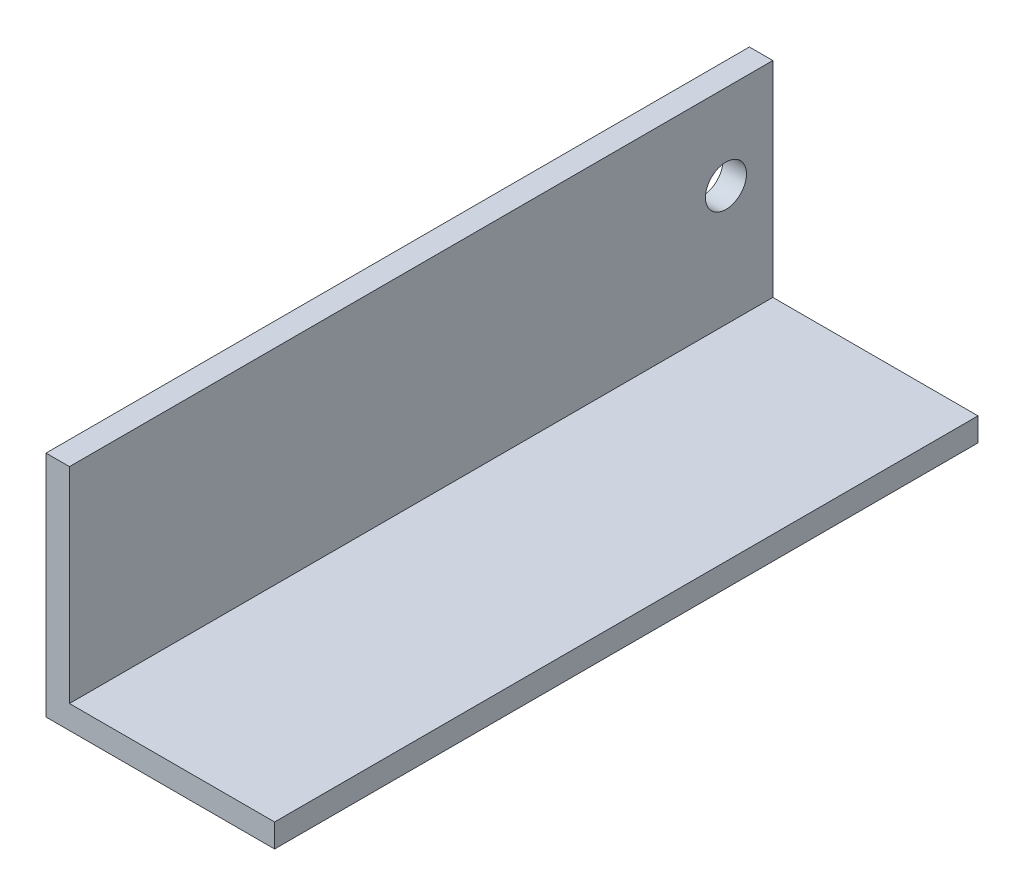
SolidWorks part; units mm, degrees
ref_plane "Front Plane" through (0, 0, 0) normal (0, 0, 1) x (1, 0, 0)
ref_plane "Top Plane" through (0, 0, 0) normal (0, 1, 0) x (1, 0, 0)
ref_plane "Right Plane" through (0, 0, 0) normal (1, 0, 0) x (0, 0, -1)
sketch "Sketch1" plane through (0, 0, 0) normal (0, 0, 1) x (1, 0, 0)
  line L0 (0, 0) -> (0, 19.5)
  line L1 (0, 19.5) -> (2, 19.5)
  line L2 (2, 19.5) -> (2, 2)
  line L3 (2, 2) -> (19.5, 2)
  line L4 (19.5, 2) -> (19.5, 0)
  line L5 (19.5, 0) -> (0, 0)
  dimension "D1" = 19.5
  dimension "D2" = 2
extrude "Boss-Extrude1" add sketch "Sketch1" along normal blind 60
sketch "Sketch2" plane through (2, 0, 0) normal (1, 0, 0) x (0, 0, -1)
  line L0 (-60, 19.5) -> (0, 19.5) construction
  line L4 (0, 2) -> (0, 19.5) construction
  circle A1 centre (-4, 12.25) radius 1.75
  point P4 (0, 0)
  point P6 (0, 0)
  point P8 (0, 0)
  dimension "D1" = 4
  dimension "D2" = 3.5
  dimension "D3" = 7.25
extrude "Cut-Extrude1" cut sketch "Sketch2" against normal through all
